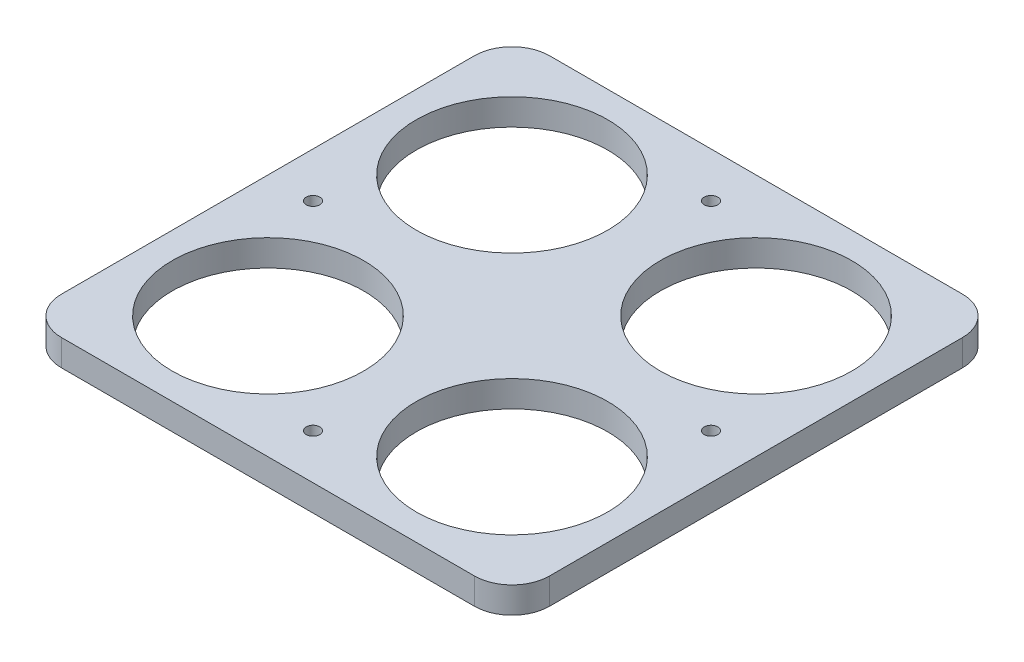
SolidWorks part; units mm, degrees
ref_plane "Front Plane" through (0, 0, 0) normal (0, 0, 1) x (1, 0, 0)
ref_plane "Top Plane" through (0, 0, 0) normal (0, 1, 0) x (1, 0, 0)
ref_plane "Right Plane" through (0, 0, 0) normal (1, 0, 0) x (0, 0, -1)
sketch "Sketch1" plane through (0, 0, 0) normal (0, 1, 0) x (1, 0, 0)
  line L0 (0, 65) -> (0, -65) construction
  line L1 (-65, -65) -> (65, -65)
  line L2 (-65, -65) -> (-65, 65)
  line L3 (-65, 65) -> (65, 65)
  line L4 (65, -65) -> (65, 65)
  line L5 (65, 0) -> (-65, 0) construction
  circle A0 centre (-32.5, 32.5) radius 25.5
  circle A1 centre (32.5, 32.5) radius 25.5
  circle A2 centre (-32.5, -32.5) radius 25.5
  circle A3 centre (32.5, -32.5) radius 25.5
  circle A7 centre (0, -53) radius 1.8
  circle A8 centre (-53, 0) radius 1.8
  circle A11 centre (0, 53) radius 1.8
  circle A12 centre (53, 0) radius 1.8
  point P4 (0, -65)
  point P6 (-65, 0)
  point P27 (2.9883, 57.8545)
  dimension "D3" = 51
  dimension "D6" = 3.6
  dimension "D1" = 130
  dimension "D2" = 130
  dimension "D4" = 32.5
  dimension "D5" = 32.5
  dimension "D7" = 53
  dimension "D8" = 53
extrude "Boss-Extrude1" add sketch "Sketch1" along normal blind 7
fillet "Fillet1" radius 10 4 edges at (-65, 3.5, -65) (65, 3.5, -65) (65, 3.5, 65) (-65, 3.5, 65)
